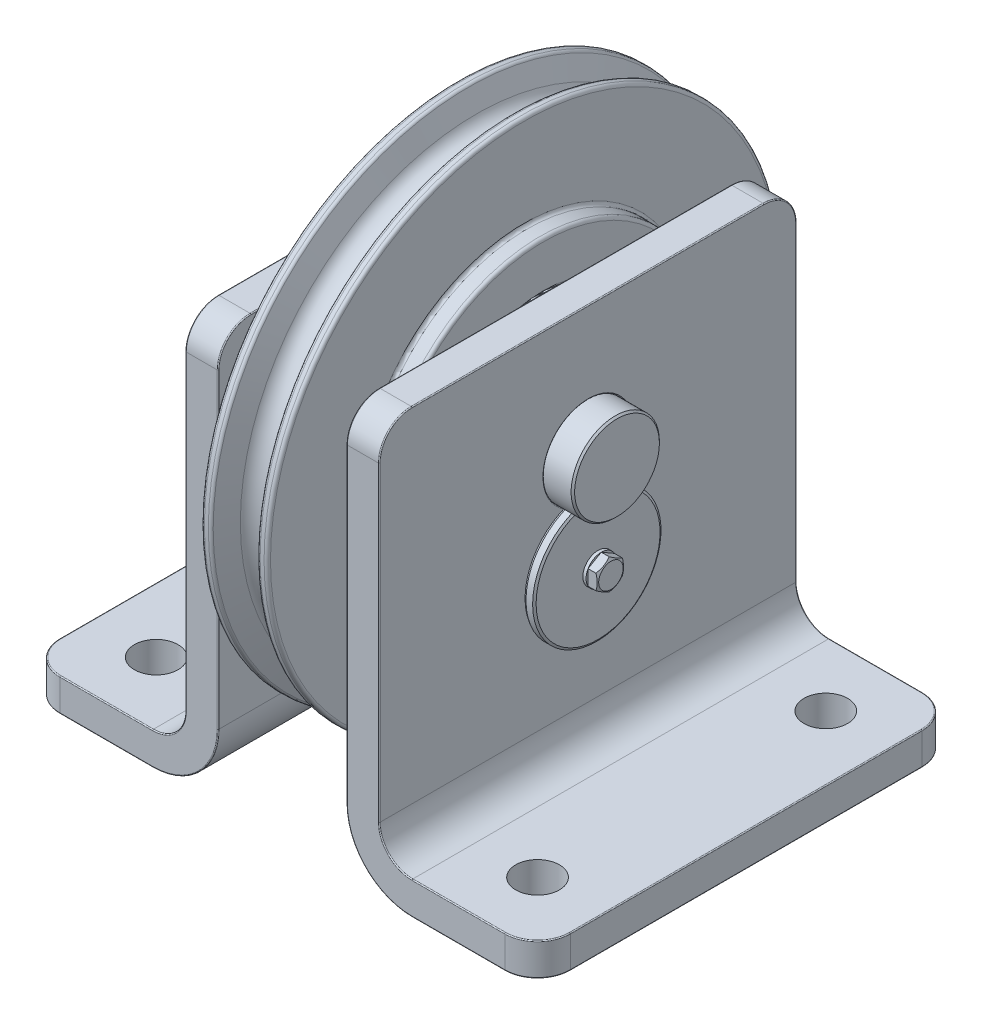
SolidWorks part; units mm, degrees
ref_plane "Front Plane" through (0, 0, 0) normal (0, 0, 1) x (1, 0, 0)
ref_plane "Top Plane" through (0, 0, 0) normal (0, 1, 0) x (1, 0, 0)
ref_plane "Right Plane" through (0, 0, 0) normal (1, 0, 0) x (0, 0, -1)
sketch "Sketch1" plane through (0, 0, 0) normal (1, 0, 0) x (0, 0, -1)
  line L1 (-82.55, 49.911) -> (82.55, 49.911)
  line L2 (-82.55, 49.911) -> (-82.55, -112.014)
  line L3 (-82.55, -112.014) -> (82.55, -112.014)
  line L4 (82.55, 49.911) -> (82.55, -112.014)
  circle A0 centre (0, 0) radius 101.6
  circle A1 centre (0, 0) radius 89.535
  circle A2 centre (0, 0) radius 17.4625
  point P7 (0, -112.014)
  point P9 (82.55, -99.06)
  point P10 (0, 101.6)
  point P11 (0, -101.6)
  point P12 (101.6, 0)
  point P13 (-101.6, 0)
  point P14 (0, 89.535)
  point P16 (101.6, 0)
  point P17 (82.55, -112.014)
  point P18 (-101.6, 0)
  point P19 (89.535, 0)
  dimension "OD" = 203.2
  dimension "ID" = 179.07
  dimension "Axle Diameter" = 34.925
  dimension "Axle Height" = 112.014
  dimension "Plate Length" = 165.1
  dimension "Plate Height" = 161.925
  dimension "Plate Thickness" = 12.954
  dimension "Overall Height" = 213.614
  dimension "Overall Length" = 203.2
sketch "Sketch2" plane through (0, 0, 0) normal (0, 0, 1) x (1, 0, 0)
  line L0 (-100.965, -112.014) -> (100.965, -112.014)
  line L3 (-100.965, -112.014) -> (-100.965, -99.06)
  line L4 (-100.965, -99.06) -> (-38.354, -99.06)
  line L5 (-38.354, -99.06) -> (-38.354, 49.911)
  line L6 (-38.354, 49.911) -> (-25.4, 49.911)
  line L7 (-25.4, 49.911) -> (-25.4, -112.014)
  line L8 (0, 101.6) -> (0, -101.6) construction
  line L9 (0, -101.6) -> (0, 101.6) construction
  line L10 (-20.701, 101.6) -> (20.701, 101.6)
  point P3 (0, -112.014)
  point P11 (6.35, 101.6)
  point P16 (0, 0)
  point P19 (0, 101.6)
  point P20 (13.081, 101.6)
  point P21 (-13.081, 101.6)
  point P23 (-6.35, 101.6)
  dimension "Width" = 201.93
  dimension "Plate Spacing" = 50.8
  dimension "Wheel Width" = 41.402
  dimension "Rope Dia" = 12.7
  dimension "Wheel OD Width" = 26.162
sketch "Sketch3" plane through (0, 0, 0) normal (0, 1, 0) x (1, 0, 0)
  line L0 (0, -82.55) -> (0, 82.55) construction
  line L1 (-100.965, 82.55) -> (-25.4, 82.55)
  line L2 (-100.965, 82.55) -> (-100.965, -82.55)
  line L3 (-100.965, -82.55) -> (-25.4, -82.55)
  line L4 (-25.4, 82.55) -> (-25.4, -82.55)
  line L5 (25.4, 82.55) -> (100.965, 82.55)
  line L6 (25.4, 82.55) -> (25.4, -82.55)
  line L7 (25.4, -82.55) -> (100.965, -82.55)
  line L8 (100.965, 82.55) -> (100.965, -82.55)
  line L9 (0, -82.55) -> (0, 82.55) construction
  line L10 (-100.965, 0) -> (100.965, 0) construction
  line L11 (-100.965, 0) -> (100.965, 0) construction
  circle A0 centre (-75.438, 57.023) radius 8.636
  circle A1 centre (-75.438, -57.023) radius 8.636
  circle A2 centre (75.438, 57.023) radius 8.636
  circle A3 centre (75.438, -57.023) radius 8.636
  point P22 (-6.35, 82.55)
  point P25 (-100.965, -82.55)
  point P26 (-100.965, 82.55)
  point P27 (100.965, 82.55)
  point P28 (100.965, -82.55)
  point P29 (-25.4, -82.55)
  point P30 (6.35, 82.55)
  point P31 (6.35, 89.535)
  point P34 (-6.35, 101.6)
  point P36 (6.35, 101.6)
  point P37 (-6.35, 89.535)
  point P38 (75.438, 65.659)
  point P42 (-75.438, -57.023)
  point P43 (-75.438, 57.023)
  point P44 (75.438, -57.023)
  point P46 (75.438, 48.387)
  point P47 (75.438, 57.023)
  dimension "Mounting Hole Diameter" = 17.272
  dimension "Mounting Hole Center to Center (A)" = 114.046
  dimension "Mounting Hole Center to Center (B)" = 150.876
sketch "Sketch4" plane through (0, 0, 0) normal (0, 0, 1) x (1, 0, 0)
  line L0 (-13.081, 101.6) -> (-13.081, 64.0842)
  line L1 (-13.081, 64.0842) -> (-20.701, 64.0842)
  line L2 (-20.701, 64.0842) -> (-20.701, 0)
  line L3 (-100.965, 0) -> (100.965, 0) construction
  line L4 (-20.701, 0) -> (20.701, 0) construction
  line L9 (-5.8216, 93.3491) -> (-9.4158, 101.6)
  line L10 (-9.4158, 101.6) -> (-13.081, 101.6)
  line L11 (0, -101.6) -> (0, 101.6) construction
  line L12 (0, -89.535) -> (0, 89.535) construction
  line L13 (13.081, 101.6) -> (13.081, 64.0842)
  line L14 (13.081, 64.0842) -> (20.701, 64.0842)
  line L15 (20.701, 64.0842) -> (20.701, 0)
  line L16 (-20.701, 101.6) -> (20.701, 101.6) construction
  line L17 (13.081, 101.6) -> (9.4158, 101.6)
  line L18 (9.4158, 101.6) -> (5.8216, 93.3491)
  line L19 (-20.701, 0) -> (20.701, 0)
  arc A0 (-5.8216, 93.3491) -> (5.8216, 93.3491) centre (0, 95.885) ccw
  point P10 (0, 89.535)
  dimension "D1" = 12.7
  dimension "D2" = 3.6652
  dimension "D3" = 128.1684
revolve "Revolve1" add sketch "Sketch4" angle 360 about L4
sketch "Sketch5" plane through (-20.701, 0, 0) normal (-1, 0, 0) x (0, 0, 1)
  circle A0 centre (0, 0) radius 44.7675
  dimension "D1" = 89.535
extrude "Cut-Extrude1" cut sketch "Sketch5" against normal through all
sketch "Sketch6" plane through (0, 0, 0) normal (1, 0, 0) x (0, 0, -1)
  circle A0 centre (0, 0) radius 44.7675 construction
  circle A1 centre (0, 0) radius 44.7675
extrude "Boss-Extrude1" add sketch "Sketch6" against normal up to surface and the other way up to surface separate body up to face at (-20.701, 0, 44.7675) other way up to face at (20.701, 0, 44.7675)
sketch "Sketch7" plane through (0, 0, 0) normal (0, 0, 1) x (1, 0, 0)
  line L0 (-25.4, 49.911) -> (-25.4, -112.014) construction
  line L1 (-38.354, 49.911) -> (-25.4, 49.911) construction
  line L2 (-38.354, -99.06) -> (-38.354, 49.911) construction
  line L3 (-100.965, -99.06) -> (-38.354, -99.06) construction
  line L4 (-100.965, -112.014) -> (-100.965, -99.06) construction
  line L5 (-25.4, 49.911) -> (-25.4, -86.106)
  line L6 (-38.354, 49.911) -> (-25.4, 49.911)
  line L7 (-38.354, -86.106) -> (-38.354, 49.911)
  line L8 (-100.965, -99.06) -> (-51.308, -99.06)
  line L9 (-100.965, -112.014) -> (-100.965, -99.06)
  line L10 (-100.965, -112.014) -> (-51.308, -112.014)
  arc A0 (-38.354, -86.106) -> (-51.308, -99.06) centre (-51.308, -86.106) cw
  arc A1 (-25.4, -86.106) -> (-51.308, -112.014) centre (-51.308, -86.106) cw
  dimension "D1" = 12.954
extrude "Boss-Extrude2" add sketch "Sketch7" along normal up to vertex (82.55 mm away) and the other way up to vertex (82.55 mm away) separate body up to point (0, -112.014, 82.55) other way up to point (0, -112.014, -82.55)
fillet "Fillet1" radius 12.954 4 edges at (-100.965, -105.537, -82.55) (-100.965, -105.537, 82.55) (-31.877, 49.911, 82.55) (-31.877, 49.911, -82.55)
sketch "Sketch8" plane through (0, -99.06, 0) normal (0, 1, 0) x (1, 0, 0)
  circle A0 centre (-75.438, -57.023) radius 8.636 construction
  circle A1 centre (-75.438, 57.023) radius 8.636 construction
  circle A2 centre (-75.438, -57.023) radius 8.636
  circle A3 centre (-75.438, 57.023) radius 8.636
extrude "Cut-Extrude2" cut sketch "Sketch8" against normal through all
sketch "Sketch9" plane through (-20.701, 0, 0) normal (-1, 0, 0) x (0, 0, 1)
  circle A0 centre (0, 0) radius 33.8667
  dimension "D1" = 67.7333
extrude "Boss-Extrude3" add sketch "Sketch9" along normal up to surface (4.699 mm away) separate body up to face at (-25.4, 1.1483, 0)
sketch "Sketch10" plane through (-38.354, 0, 0) normal (-1, 0, 0) x (0, 0, 1)
  circle A0 centre (0, 0) radius 17.4625 construction
  circle A1 centre (0, 0) radius 17.4625
extrude "Cut-Extrude3" cut sketch "Sketch10" against normal through all
sketch "Sketch11" plane through (0, 0, 0) normal (1, 0, 0) x (0, 0, -1)
  circle A0 centre (0, 0) radius 17.4625 construction
  circle A1 centre (0, 0) radius 17.4625
extrude "Boss-Extrude4" add sketch "Sketch11" along normal mid plane 99.7204 separate body
sketch "Sketch12" plane through (-38.354, 0, 0) normal (-1, 0, 0) x (0, 0, 1)
  circle A0 centre (0, -38.1) radius 25.4
  circle A1 centre (0, 0) radius 17.4625 construction
  circle A2 centre (0, 0) radius 17.4625
  circle M2 centre (0, 0) radius 17.4625
  dimension "Washer Diameter" = 50.8
  dimension "Washer Center Distance" = 38.1
extrude "Boss-Extrude5" add sketch "Sketch12" along normal blind 4.0132 separate body contours A0 M2 | A0 M2
sketch "Sketch13" plane through (-38.354, 0, 0) normal (-1, 0, 0) x (0, 0, 1)
  line L1 (-25.4, -12.7) -> (25.4, -12.7)
  line L2 (-25.4, -12.7) -> (-25.4, -63.5)
  line L3 (-25.4, -63.5) -> (25.4, -63.5)
  line L4 (25.4, -12.7) -> (25.4, -63.5)
  circle A0 centre (0, -38.1) radius 25.4 construction
  circle A1 centre (0, -38.1) radius 25.4 construction
extrude "Cut-Extrude4" cut sketch "Sketch13" along normal up to surface (4.0132 mm away) up to face at (-42.3672, -38.1, 25.4)
mirror "Mirror1" about plane through (0, 0, 0) normal (1, 0, 0) of "Cut-Extrude4"
sketch "Sketch14" plane through (-42.3672, 0, 0) normal (-1, 0, 0) x (0, 0, 1)
  circle A0 centre (0, -38.1) radius 6.0325
  circle A1 centre (0, -38.1) radius 25.4 construction
  dimension "D1" = 12.065
extrude "Boss-Extrude6" add sketch "Sketch14" along normal blind 1.27 separate body
sketch "Sketch15" plane through (-43.6372, 0, 0) normal (-1, 0, 0) x (0, 0, 1)
  line L1 (5.2243, -35.0837) -> (0, -32.0675)
  line L2 (0, -32.0675) -> (-5.2243, -35.0838)
  line L3 (-5.2243, -35.0838) -> (-5.2243, -41.1162)
  line L4 (-5.2243, -41.1162) -> (0, -44.1325)
  line L5 (0, -44.1325) -> (5.2243, -41.1162)
  line L6 (5.2243, -41.1162) -> (5.2243, -35.0837)
  circle A0 centre (0, -38.1) radius 5.2243 construction
  circle A1 centre (0, -38.1) radius 6.0325 construction
extrude "Boss-Extrude7" add sketch "Sketch15" along normal blind 3.81 separate body
sketch "Sketch16" plane through (-47.4472, 0, 0) normal (-1, 0, 0) x (0, 0, 1)
  circle A0 centre (0, -38.1) radius 4.8433
  circle A2 centre (0, -38.1) radius 5.2243 construction
  dimension "D1" = 0.381
extrude "Cut-Extrude5" cut sketch "Sketch16" against normal through all draft 60 flip side to cut
chamfer "Chamfer1" distance 0.6985 angle 45 2 edges at (-49.8602, 0, -17.4625) (49.8602, 0, -17.4625)
sketch "Sketch17" plane through (-49.8602, 0, 0) normal (-1, 0, 0) x (0, 0, 1)
  circle A0 centre (0, 0) radius 1.27
  dimension "D1" = 2.54
extrude "Cut-Extrude6" cut sketch "Sketch17" against normal up to vertex (24.4602 mm away) up to point (-25.4, 49.911, 0)
chamfer "Chamfer2" distance 0.508 angle 60 2 edges at (-42.3672, -38.1, 25.4) (-38.354, -38.1, 25.4)
fillet "Fillet2" radius 0.381 25 edges at (-97.1709, -112.014, 78.7559) (-100.965, -112.014, 0) (-97.1709, -112.014, -78.7559) (-69.6595, -112.014, -82.55) (-32.9883, -104.4257, -82.55) (-25.4, -24.5745, -82.55) (-25.4, 46.1169, -78.7559) (-25.4, 49.911, 0) (-25.4, 46.1169, 78.7559) (-25.4, -24.5745, 82.55) (-32.9883, -104.4257, 82.55) (-38.354, 46.1169, 78.7559) (-38.354, -24.5745, 82.55) (-42.1481, -95.2659, 82.55) (-69.6595, -99.06, 82.55) (-97.1709, -99.06, 78.7559) (-100.965, -99.06, 0) (-97.1709, -99.06, -78.7559) (-69.6595, -99.06, -82.55) (-42.1481, -95.2659, -82.55) (-38.354, -24.5745, -82.55) (-38.354, 46.1169, -78.7559) (-69.6595, -112.014, 82.55) (-38.354, 49.911, 0) (-38.354, 0, 17.4625)
chamfer "Chamfer3" distance 0.254 angle 60 2 edges at (-20.701, 0, 33.8667) (-25.4, -33.8667, 0)
fillet "Fillet3" radius 1.27 10 edges at (20.701, 0, 64.0842) (13.081, 0, 64.0842) (13.081, 0, 101.6) (9.4158, 0, 101.6) (-9.4158, 0, 101.6) (-13.081, 0, 101.6) (-13.081, 0, 64.0842) (-20.701, 0, 64.0842) (20.701, 0, 44.7675) (-20.701, 0, 44.7675)
chamfer "Chamfer4" distance 0.508 angle 45 2 edges at (20.701, 0, 44.7675) (-20.701, 0, -44.7675)
mirror "Mirror2" about plane through (0, 0, 0) normal (1, 0, 0) of bodies 109 116 114 112
equation "\"D1@Sketch4\"=\"Rope Dia@Sketch2\""
equation "\"D3@Sketch4\"=\"Overall Height@Sketch1\"*.6"
equation "\"D1@Sketch7\" = \"Plate Thickness@Sketch1\""
equation "\"D1@Fillet1\"=\"Plate Thickness@Sketch1\""
equation "\"D1@Sketch9\" = \"OD@Sketch1\" / 3"
equation "\"D1@Chamfer1\"=\"Axle Diameter@Sketch1\"*.02"
equation "\"D1@Sketch5\" = \"ID@Sketch1\" / 2"
equation "\"D1@Boss-Extrude4\" =  ( \"Plate Spacing@Sketch2\" +  ( \"Plate Thickness@Sketch1\" * 2 )  )  * 1.3"
